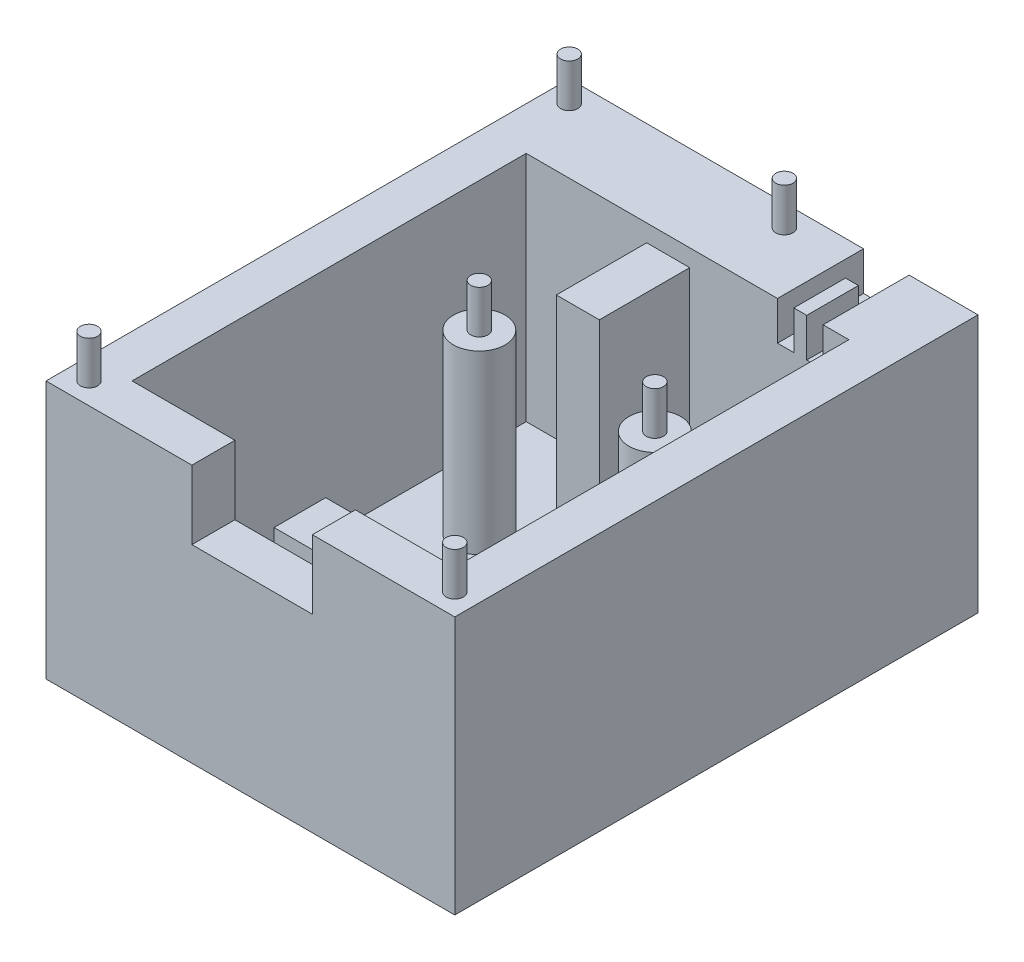
SolidWorks part; units mm, degrees
ref_plane "前视基准面" through (0, 0, 0) normal (0, 0, 1) x (1, 0, 0)
ref_plane "上视基准面" through (0, 0, 0) normal (0, 1, 0) x (1, 0, 0)
ref_plane "右视基准面" through (0, 0, 0) normal (1, 0, 0) x (0, 0, -1)
other "Configuration Table"
sketch "草图1" plane through (0, 0, 0) normal (0, 1, 0) x (1, 0, 0)
  line L1 (-50.0333, 28.8167) -> (-2.5333, 28.8167)
  line L2 (-50.0333, 28.8167) -> (-50.0333, -31.9833)
  line L3 (-50.0333, -31.9833) -> (-2.5333, -31.9833)
  line L4 (-2.5333, 28.8167) -> (-2.5333, -31.9833)
  dimension "D1" = 47.5
  dimension "D2" = 60.8
extrude "凸台-拉伸1" add sketch "草图1" along normal blind 30
sketch "草图2" plane through (0, 30, 0) normal (0, 1, 0) x (1, 0, 0)
  line L0 (-2.5333, -31.9833) -> (-2.5333, 28.8167) construction
  line L1 (-2.5333, 28.8167) -> (-50.0333, 28.8167) construction
  line L2 (-50.0333, 28.8167) -> (-50.0333, -31.9833) construction
  line L3 (-50.0333, -31.9833) -> (-2.5333, -31.9833) construction
  circle A0 centre (-22.5333, 26.3167) radius 1
  circle A1 centre (-47.5333, 26.3167) radius 1
  circle A2 centre (-47.5333, -29.4833) radius 1
  circle A3 centre (-5.0333, -29.4833) radius 1
  dimension "D1" = 20
  dimension "D3" = 2.5
  dimension "D5" = 2.5
  dimension "D7" = 2.5
  dimension "D2" = 2.5
  dimension "D4" = 2.5
  dimension "D6" = 2.5
  dimension "D8" = 2.5
extrude "凸台-拉伸3" add sketch "草图2" along normal blind 5
sketch "草图3" plane through (0, 30, 0) normal (0, 1, 0) x (1, 0, 0)
  line L0 (-50.0333, 28.8167) -> (-50.0333, -31.9833) construction
  line L1 (-45.0333, 18.8167) -> (-7.5333, 18.8167)
  line L2 (-45.0333, 18.8167) -> (-45.0333, -26.9833)
  line L3 (-45.0333, -26.9833) -> (-7.5333, -26.9833)
  line L4 (-7.5333, 18.8167) -> (-7.5333, -26.9833)
  line L5 (-2.5333, -31.9833) -> (-2.5333, 28.8167) construction
  line L6 (-2.5333, 28.8167) -> (-50.0333, 28.8167) construction
  line L7 (-50.0333, -31.9833) -> (-2.5333, -31.9833) construction
  dimension "D1" = 5
  dimension "D2" = 5
  dimension "D3" = 10
  dimension "D4" = 5
extrude "切除-拉伸1" cut sketch "草图3" against normal blind 27
sketch "草图4" plane through (0, 30, 0) normal (0, 1, 0) x (1, 0, 0)
  line L0 (-45.0333, -26.9833) -> (-7.5333, -26.9833) construction
  line L1 (-33.0833, -26.9833) -> (-19.0833, -26.9833)
  line L2 (-33.0833, -26.9833) -> (-33.0833, -31.9833)
  line L3 (-33.0833, -31.9833) -> (-19.0833, -31.9833)
  line L4 (-19.0833, -26.9833) -> (-19.0833, -31.9833)
  line L5 (-50.0333, -31.9833) -> (-2.5333, -31.9833) construction
  line L6 (-2.5333, -31.9833) -> (-2.5333, 28.8167) construction
  dimension "D1" = 16.55
  dimension "D2" = 14
extrude "切除-拉伸2" cut sketch "草图4" against normal blind 8
sketch "草图5" plane through (0, 3, 0) normal (0, 1, 0) x (1, 0, 0)
  line L0 (-2.5333, -31.9833) -> (-2.5333, 28.8167) construction
  line L2 (-2.5333, 28.8167) -> (-50.0333, 28.8167) construction
  line L3 (-50.0333, 28.8167) -> (-50.0333, -31.9833) construction
  line L4 (-45.0333, -26.9833) -> (-7.5333, -26.9833) construction
  line L5 (-28.5333, -20.9833) -> (-22.5333, -20.9833)
  line L6 (-28.5333, -20.9833) -> (-28.5333, -26.9833)
  line L7 (-28.5333, -26.9833) -> (-22.5333, -26.9833)
  line L8 (-22.5333, -20.9833) -> (-22.5333, -26.9833)
  line L9 (-7.5333, -26.9833) -> (-7.5333, 18.8167) construction
  circle A0 centre (-16.0833, 4.8167) radius 3
  circle A1 centre (-36.4833, 4.8167) radius 3
  point P16 (-25.5333, -20.9833)
  point P19 (-28.5333, -23.9833)
  dimension "D1" = 13.55
  dimension "D3" = 13.55
  dimension "D2" = 24
  dimension "D4" = 24
  dimension "D5" = 6
  dimension "D6" = 15
  dimension "D7" = 6
  dimension "D8" = 31.8
extrude "凸台-拉伸4" add sketch "草图5" along normal blind 20.5
sketch "草图6" plane through (0, 3, 0) normal (0, 1, 0) x (1, 0, 0)
  line L0 (-7.5333, 18.8167) -> (-45.0333, 18.8167) construction
  line L1 (-31.0333, 18.8167) -> (-26.0333, 18.8167)
  line L2 (-31.0333, 18.8167) -> (-31.0333, 8.3167)
  line L3 (-31.0333, 8.3167) -> (-26.0333, 8.3167)
  line L4 (-26.0333, 18.8167) -> (-26.0333, 8.3167)
  line L5 (-45.0333, 18.8167) -> (-45.0333, -26.9833) construction
  circle A1 centre (-36.4833, 4.8167) radius 3
  circle A2 centre (-36.4833, 4.8167) radius 3 construction
  dimension "D1" = 0
  dimension "D2" = 3.5
  dimension "D3" = 5
  dimension "D4" = 0
  dimension "D5" = 14
extrude "凸台-拉伸6" add sketch "草图6" along normal blind 25
sketch "草图7" plane through (0, 23.5, 0) normal (0, 1, 0) x (1, 0, 0)
  circle A0 centre (-36.4833, 4.8167) radius 1
  circle A1 centre (-16.0833, 4.8167) radius 1
extrude "凸台-拉伸7" add sketch "草图7" along normal blind 5
sketch "草图12" plane through (0, 0, -28.8167) normal (0, 0, -1) x (-1, 0, 0)
  line L0 (2.5333, 30) -> (50.0333, 30) construction
  line L1 (10.5333, 30) -> (15.8333, 30)
  line L2 (10.5333, 30) -> (10.5333, 25.5)
  line L3 (10.5333, 25.5) -> (15.8333, 25.5)
  line L4 (15.8333, 30) -> (15.8333, 25.5)
  line L5 (2.5333, 30) -> (2.5333, 0) construction
  dimension "D1" = 8
  dimension "D2" = 5.3
  dimension "D3" = 4.5
extrude "切除-拉伸5" cut sketch "草图12" against normal blind 10
sketch "草图13" plane through (0, 25.5, 0) normal (0, 1, 0) x (1, 0, 0)
  line L0 (-10.5333, 18.8167) -> (-15.8333, 18.8167) construction
  line L1 (-13.9333, 24.8167) -> (-12.4333, 24.8167)
  line L2 (-13.9333, 24.8167) -> (-13.9333, 18.8167)
  line L3 (-13.9333, 18.8167) -> (-12.4333, 18.8167)
  line L4 (-12.4333, 24.8167) -> (-12.4333, 18.8167)
  line L5 (-10.5333, 28.8167) -> (-15.8333, 28.8167) construction
  line L6 (-10.5333, 18.8167) -> (-10.5333, 28.8167) construction
  point P6 (-13.1833, 24.8167)
  dimension "D1" = 4
  dimension "D2" = 1.9
  dimension "D3" = 1.5
extrude "凸台-拉伸8" add sketch "草图13" along normal blind 4.5
